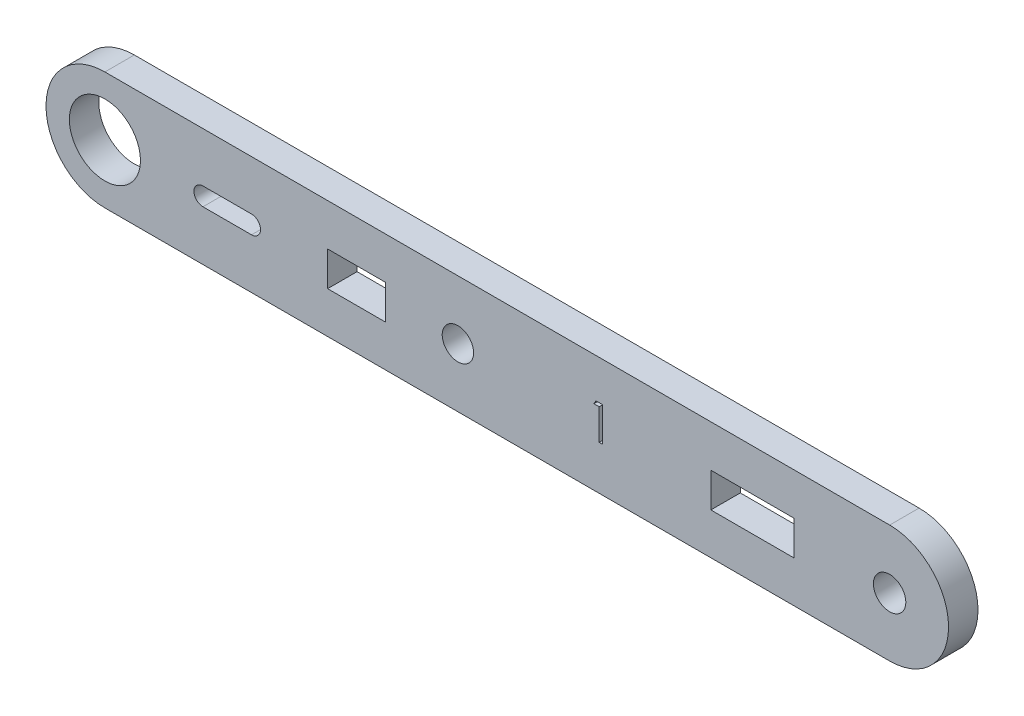
SolidWorks part; units mm, degrees
ref_plane "前视基准面" through (0, 0, 0) normal (0, 0, 1) x (1, 0, 0)
ref_plane "上视基准面" through (0, 0, 0) normal (0, 1, 0) x (1, 0, 0)
ref_plane "右视基准面" through (0, 0, 0) normal (1, 0, 0) x (0, 0, -1)
ref_plane "基准面4" through (0, 0, 3) normal (0, 0, 1) x (1, 0, 0)
sketch "草图1" plane through (0, 0, 3) normal (0, 0, 1) x (1, 0, 0)
  line L0 (-26.6486, 7.7302) -> (-20.7382, 7.7302)
  line L1 (-20.7382, 7.7302) -> (-20.7382, 4.224)
  line L2 (-20.7382, 4.224) -> (-26.6486, 4.224)
  line L3 (-26.6486, 4.224) -> (-26.6486, 7.7302)
  line L4 (12.3992, 7.7302) -> (20.868, 7.7302)
  line L5 (20.868, 7.7302) -> (20.868, 4.224)
  line L6 (20.868, 4.224) -> (12.3992, 4.224)
  line L7 (12.3992, 4.224) -> (12.3992, 7.7302)
  line L8 (30.6182, 12) -> (-49.3435, 12)
  line L9 (-49.3435, 0) -> (30.6182, 0)
  line L10 (-34.4047, 5.1001) -> (-39.3523, 5.1001)
  line L11 (-39.3523, 6.9343) -> (-34.4047, 6.9343)
  arc A0 (-49.3435, 12) -> (-49.3435, 0) centre (-49.3435, 6) ccw
  arc A1 (30.6182, 0) -> (30.6182, 12) centre (30.6182, 6) ccw
  circle A2 centre (30.6116, 6.0001) radius 1.65
  circle A4 centre (-49.3435, 6) radius 3.62
  arc A5 (-34.4047, 6.9343) -> (-34.4047, 5.1001) centre (-34.4047, 6.0172) cw
  arc A6 (-39.3523, 5.1001) -> (-39.3523, 6.9343) centre (-39.3523, 6.0172) cw
extrude "凸台-拉伸1" add sketch "草图1" against normal blind 3
sketch "草图2" plane through (0, 0, 3) normal (0, 0, 1) x (1, 0, 0)
  circle A0 centre (-13.3753, 6.0002) radius 1.6
  dimension "D1" = 3.2
extrude "切除-拉伸1" cut sketch "草图2" against normal through all
sketch "草图3" plane through (0, 0, 3) normal (0, 0, 1) x (1, 0, 0)
  text T0 "1"
extrude "切除-拉伸2" cut sketch "草图3" against normal blind 1
